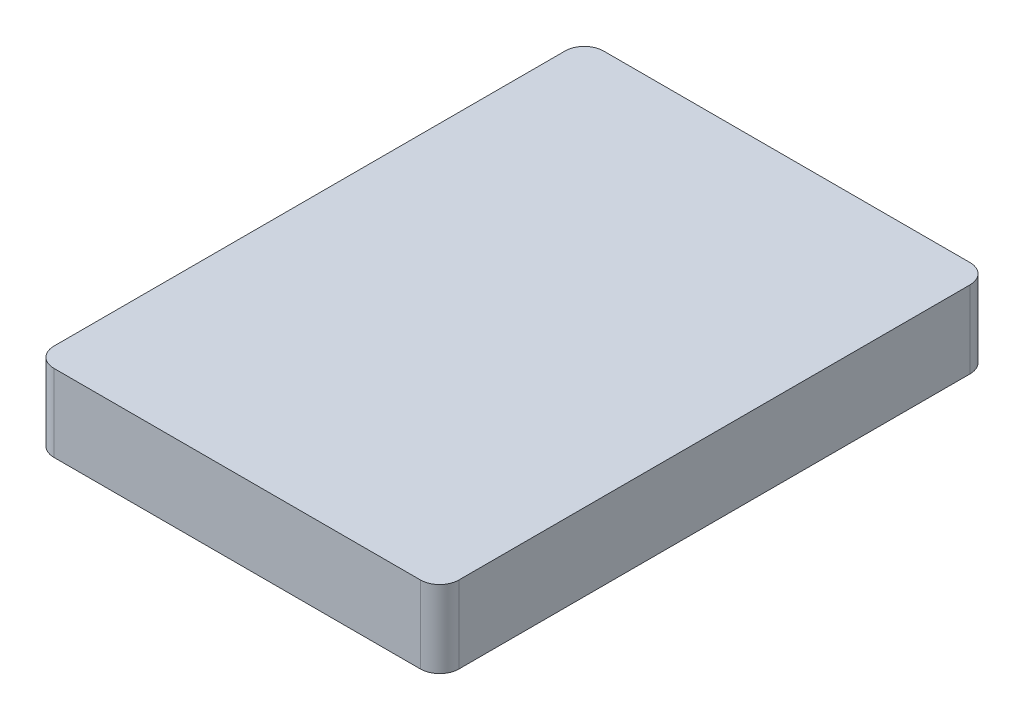
SolidWorks part; units mm, degrees
ref_plane "Front Plane" through (0, 0, 0) normal (0, 0, 1) x (1, 0, 0)
ref_plane "Top Plane" through (0, 0, 0) normal (0, 1, 0) x (1, 0, 0)
ref_plane "Right Plane" through (0, 0, 0) normal (1, 0, 0) x (0, 0, -1)
sketch "Sketch1" plane through (0, 0, 0) normal (0, 1, 0) x (1, 0, 0)
  line L1 (0, 0) -> (42, 0)
  line L2 (0, 0) -> (0, 57)
  line L3 (0, 57) -> (42, 57)
  line L4 (42, 0) -> (42, 57)
  dimension "D1" = 42
  dimension "D2" = 57
extrude "Boss-Extrude1" add sketch "Sketch1" along normal blind 8
fillet "Fillet1" radius 2 4 edges at (0, 4, -57) (42, 4, -57) (42, 4, 0) (0, 4, 0)
